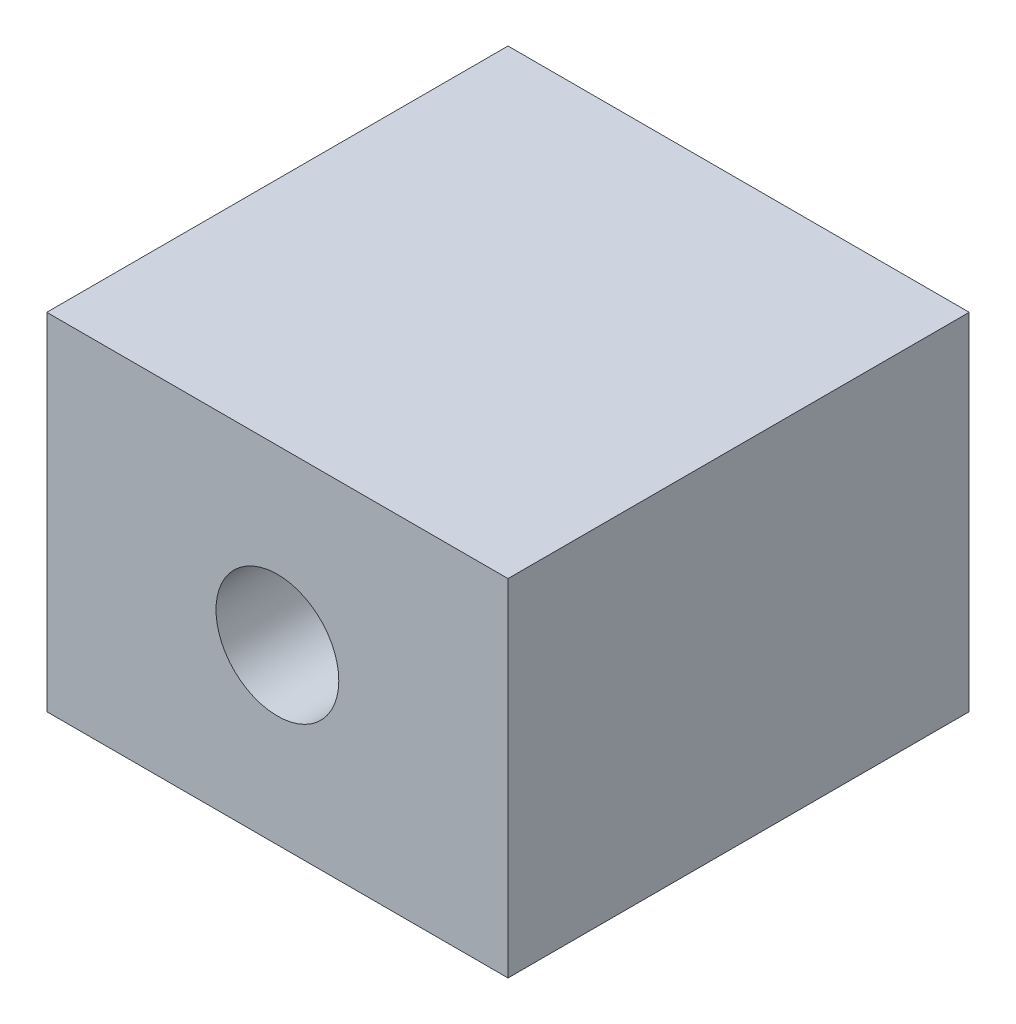
SolidWorks part; units mm, degrees
ref_plane "Front Plane" through (0, 0, 0) normal (0, 0, 1) x (1, 0, 0)
ref_plane "Top Plane" through (0, 0, 0) normal (0, 1, 0) x (1, 0, 0)
ref_plane "Right Plane" through (0, 0, 0) normal (1, 0, 0) x (0, 0, -1)
sketch "Sketch1" plane through (0, 0, 0) normal (0, 1, 0) x (1, 0, 0)
  line L0 (10.6537, -7.62) -> (23.3537, -7.62)
  line L4 (23.3537, -7.62) -> (23.3537, 2.54)
  line L6 (10.6537, 2.54) -> (23.3537, 2.54)
  line L10 (10.6537, 2.54) -> (10.6537, -7.62)
  point P0 (0, 0)
  point P9 (23.3537, -7.62)
  dimension "D1" = 10.16
  dimension "D2" = 12.7
extrude "Boss-Extrude1" add sketch "Sketch1" along normal blind 7.62
sketch "Sketch2" [suppressed] plane through (10.4887, 0, 0) normal (-1, 0, 0) x (0, 0, 1)
  line L0 (-12.7, 6.35) -> (-12.7, 0) construction
  line L1 (6.35, 6.35) -> (6.35, 0) construction
  point P0 (-8.89, 3.175)
  point P1 (2.54, 3.175)
  point P6 (-12.7, 3.175)
  dimension "D1" = 3.81
  dimension "D2" = 3.81
hole_wizard "#6 Clearance Hole1" [suppressed] positions "Sketch3" profile "Sketch4" hole size "#6" standard "ANSI Inch"
sketch "Sketch3" [suppressed] plane through (10.4887, 0, 0) normal (-1, 0, 0) x (0, 0, 1)
  point P0 (-8.89, 3.175)
  point P3 (2.54, 3.175)
sketch "Sketch4" plane through (10.4887, 3.175, -8.89) normal (0, 1, 0) x (0, 0, 1)
  line L0 (0, 0) -> (0, 7.874)
  line L1 (0, 7.874) -> (1.8986, 6.7332)
  line L2 (1.8986, 6.7332) -> (1.8986, 0)
  line L5 (1.8986, 0) -> (0, 0)
  line L10 (0, 7.874) -> (-1.8987, 6.7332) construction
  line L11 (0, -6.35) -> (0, 107.95) construction
  dimension "Hole Dia." = 3.7973
  dimension "Hole Depth" = 7.874
  dimension "Drill Angle" = 118
fillet "Fillet1" [suppressed] radius 0.508
sketch "Sketch11" plane through (0, 0, 7.62) normal (0, 0, 1) x (1, 0, 0)
  line L0 (10.6537, 0) -> (23.3537, 0) construction
  line L1 (10.6537, 7.62) -> (13.1937, 7.62)
  line L2 (10.6537, 7.62) -> (10.6537, 0)
  line L3 (10.6537, 0) -> (13.1937, 0)
  line L4 (13.1937, 7.62) -> (13.1937, 0)
  dimension "D1" = 2.54
extrude "Cut-Extrude1" cut sketch "Sketch11" against normal through all
sketch "Sketch5" plane through (24.3726, 0, 7.62) normal (0, 0, -1) x (-1, 0, 0)
  line L2 (11.1789, 7.62) -> (1.0189, 7.62) construction
  line L3 (1.0189, 7.62) -> (1.0189, 0) construction
  point P0 (6.0989, 3.81)
  point P11 (6.0989, 7.62)
  point P14 (1.0189, 3.81)
hole_wizard "#6-32 Tapped Hole1" positions "Sketch8" profile "Sketch10" tap size "#6-32" standard "ANSI Inch" end condition up to next
sketch "Sketch8" plane through (0, 0, 7.62) normal (0, 0, 1) x (1, 0, 0)
  point P0 (18.2737, 3.81)
sketch "Sketch10" plane through (18.2737, 3.81, 7.62) normal (1, 0, 0) x (0, -1, 0)
  line L0 (0, 0) -> (0, 10.16)
  line L1 (0, 10.16) -> (1.3525, 10.16)
  line L2 (1.3525, 10.16) -> (1.3525, 0)
  line L5 (1.3525, 0) -> (0, 0)
  line L11 (0, -6.35) -> (0, 107.95) construction
  dimension "Thru Tap Drill Dia." = 2.7051
  dimension "Thru Tap Drill Depth" = 10.16
cosmetic thread "Hole Thread1" parameters "D2"=3.5052
